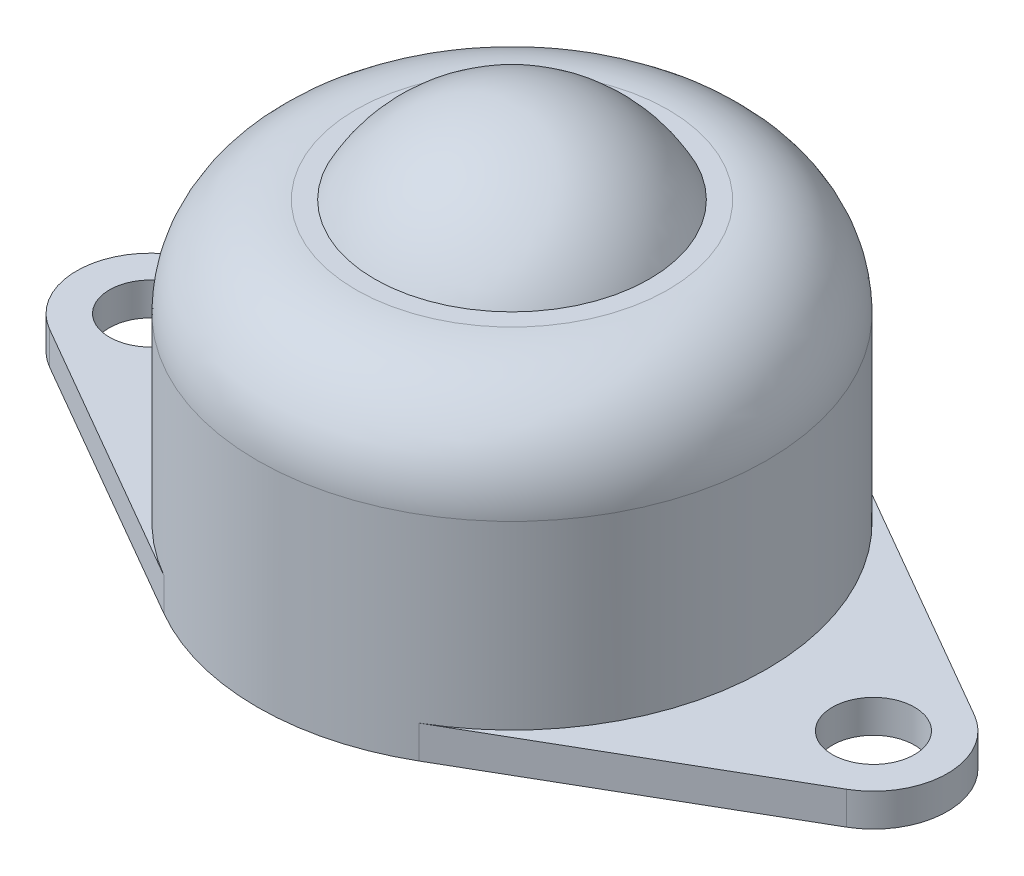
SolidWorks part; units mm, degrees
ref_plane "前视基准面" through (0, 0, 0) normal (0, 0, 1) x (1, 0, 0)
ref_plane "上视基准面" through (0, 0, 0) normal (0, 1, 0) x (1, 0, 0)
ref_plane "右视基准面" through (0, 0, 0) normal (1, 0, 0) x (0, 0, -1)
sketch "草图1" plane through (0, 0, 0) normal (0, 0, 1) x (1, 0, 0)
  line L0 (0, 0) -> (0, 0.3826) construction
  line L1 (0, 0) -> (0, 27.1726) construction
  line L2 (0, -14.5) -> (15.5, -14.5)
  line L3 (15.5, -14.5) -> (15.5, -1.5)
  line L4 (9.5, 4.5) -> (8.3666, 4.5)
  line L5 (0, 9.5) -> (0, -14.5)
  arc A0 (8.3666, 4.5) -> (0, 9.5) centre (0, 0) ccw
  arc A1 (15.5, -1.5) -> (9.5, 4.5) centre (9.5, -1.5) ccw
  point P12 (15.5, 4.5)
  dimension "D1" = 19
  dimension "D5" = 6
  dimension "D2" = 24
  dimension "D3" = 31
  dimension "D4" = 19
revolve "旋转1" add sketch "草图1" angle 360 about L5
sketch "草图2" plane through (0, -14.5, 0) normal (0, -1, 0) x (1, 0, 0)
  line L0 (0, 0) -> (0, 29.2866) construction
  line L1 (-24.25, 3.8971) -> (-7.75, 13.4234)
  line L2 (0, 0) -> (-28.944, 0) construction
  line L3 (-24.25, -3.8971) -> (-7.75, -13.4234)
  line L4 (24.25, -3.8971) -> (7.75, -13.4234)
  line L5 (24.25, 3.8971) -> (7.75, 13.4234)
  circle A0 centre (-22, 0) radius 2.5
  circle A1 centre (22, 0) radius 2.5
  arc A2 (-24.25, 3.8971) -> (-24.25, -3.8971) centre (-22, 0) ccw
  arc A3 (7.75, -13.4234) -> (-7.75, -13.4234) centre (0, 0) cw
  arc A4 (24.25, 3.8971) -> (24.25, -3.8971) centre (22, 0) cw
  circle A5 centre (0, 0) radius 15.5 construction
  arc A6 (7.75, 13.4234) -> (-7.75, 13.4234) centre (0, 0) ccw
  dimension "D1" = 44
  dimension "D2" = 5
  dimension "D3" = 53
extrude "凸台-拉伸1" add sketch "草图2" against normal blind 2
